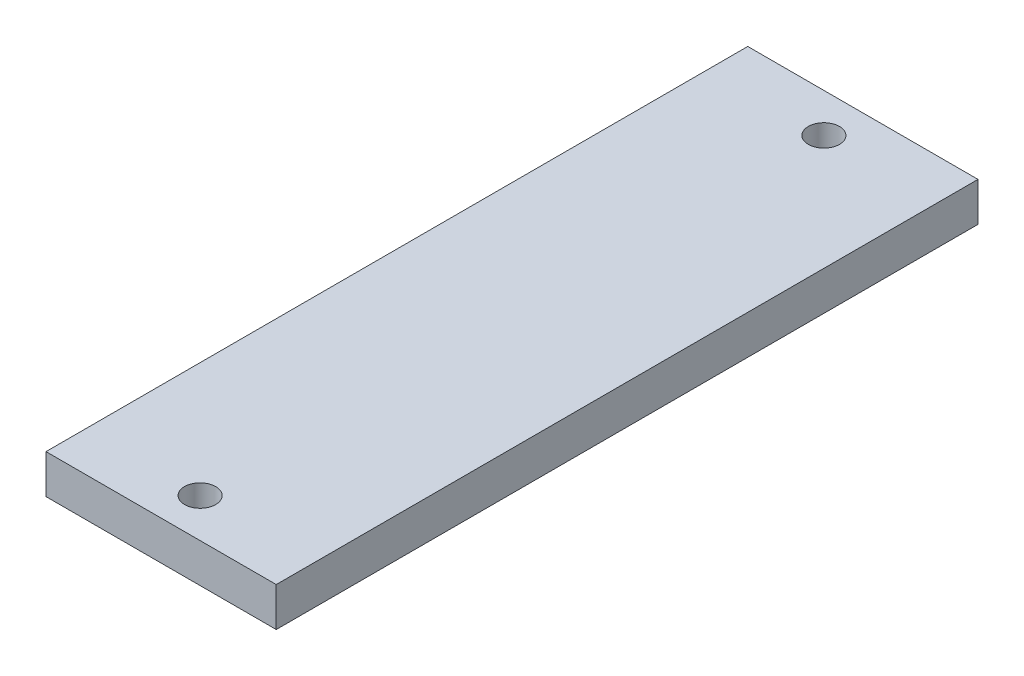
SolidWorks part; units mm, degrees
material "6061 Alloy"
ref_plane "Front" through (0, 0, 0) normal (0, 0, 1) x (1, 0, 0)
ref_plane "Top" through (0, 0, 0) normal (0, 1, 0) x (1, 0, 0)
ref_plane "Right" through (0, 0, 0) normal (1, 0, 0) x (0, 0, -1)
sketch "Sketch1" plane through (0, 0, 0) normal (0, 1, 0) x (1, 0, 0)
  line L1 (-18.75, -57.15) -> (18.75, -57.15)
  line L2 (-18.75, -57.15) -> (-18.75, 57.15)
  line L3 (-18.75, 57.15) -> (18.75, 57.15)
  line L4 (18.75, -57.15) -> (18.75, 57.15)
  line L5 (-18.75, -57.15) -> (18.75, 57.15) construction
  line L6 (-18.75, 57.15) -> (18.75, -57.15) construction
  point P0 (0, 0)
  dimension "D1" = 37.5
  dimension "D2" = 114.3
extrude "Boss-Extrude1" add sketch "Sketch1" along normal blind 6.35
sketch "Sketch3" plane through (0, 6.35, 0) normal (0, 1, 0) x (1, 0, 0)
  line L0 (18.75, 57.15) -> (-18.75, 57.15) construction
  line L1 (-18.75, 0) -> (18.75, 0) construction
  line L2 (-18.75, 57.15) -> (-18.75, -57.15) construction
  line L3 (18.75, -57.15) -> (18.75, 57.15) construction
  circle A4 centre (0, 50.8) radius 2.54
  circle A5 centre (0, -50.8) radius 2.54
  dimension "D1" = 5.08
  dimension "D2" = 6.35
extrude "Cut-Extrude2" cut sketch "Sketch3" against normal blind 9.525
